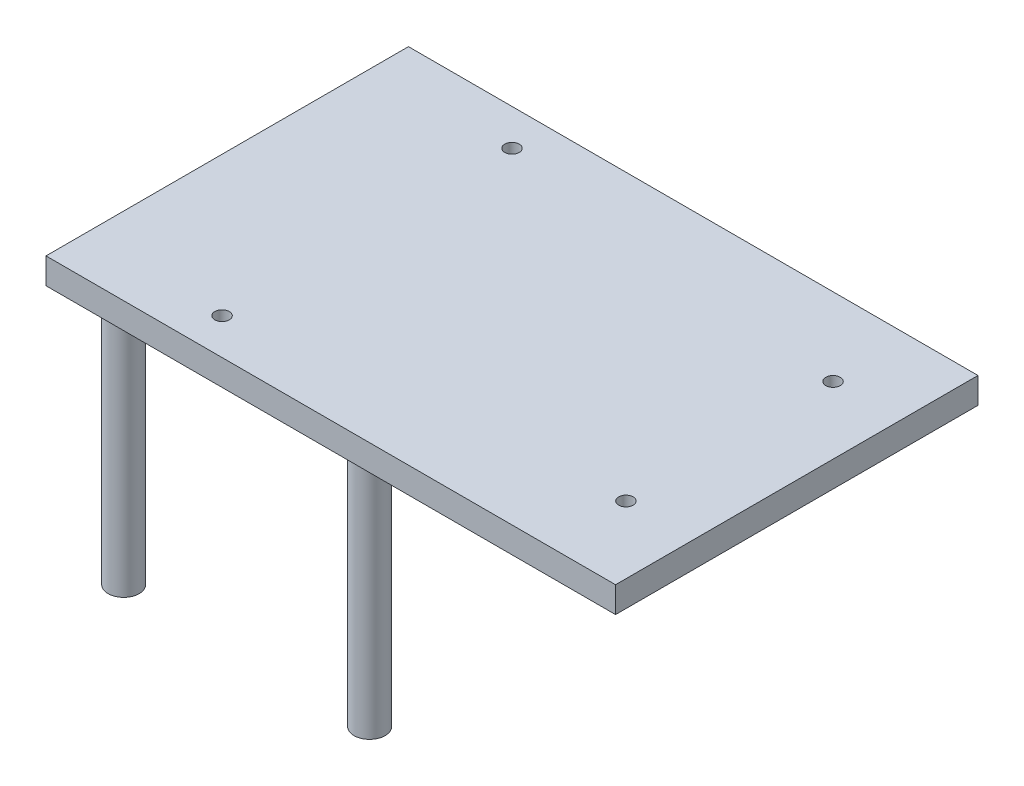
SolidWorks part; units mm, degrees
other "Markup1"
sketch "Sketch3" plane through (-55, 0, -35) normal (0, 1, 0) x (1, 0, 0)
other "DetailItem1"
ref_plane "Front Plane" through (0, 0, 0) normal (0, 0, 1) x (1, 0, 0)
ref_plane "Top Plane" through (0, 0, 0) normal (0, 1, 0) x (1, 0, 0)
ref_plane "Right Plane" through (0, 0, 0) normal (1, 0, 0) x (0, 0, -1)
sketch "Sketch1" plane through (0, 0, 0) normal (0, 1, 0) x (1, 0, 0)
  line L1 (-55, 35) -> (55, 35)
  line L2 (-55, 35) -> (-55, -35)
  line L3 (-55, -35) -> (55, -35)
  line L4 (55, 35) -> (55, -35)
  line L5 (-55, 35) -> (55, -35) construction
  line L6 (-55, -35) -> (55, 35) construction
  dimension "D1" = 70
  dimension "D2" = 110
extrude "Boss-Extrude2" add sketch "Sketch1" against normal blind 5
sketch "Sketch2" plane through (0, 0, 0) normal (0, 1, 0) x (1, 0, 0)
  line L0 (-28, 28) -> (-28, -28) construction
  line L1 (42, 20) -> (42, -20) construction
  circle A8 centre (-28, 28) radius 1.4
  circle A9 centre (42, 20) radius 1.4
  circle A10 centre (-28, -28) radius 1.4
  circle A11 centre (42, -20) radius 1.4
  point P12 (42, 0)
  point P15 (-28, 0)
  dimension "D1" = 56
  dimension "D5" = 2.8
  dimension "D6" = 2.8
  dimension "D7" = 2.8
  dimension "D8" = 2.8
  dimension "D2" = 40
  dimension "D3" = 28
  dimension "D4" = 42
extrude "Cut-Extrude1" cut sketch "Sketch2" against normal blind 5
sketch "Sketch4" plane through (0, -5, 0) normal (0, -1, 0) x (1, 0, 0)
  line L0 (-55, -35) -> (-55, 35) construction
  line L1 (-55, 35) -> (55, 35) construction
  line L3 (2.75, 0) -> (-2.75, 0) construction
  circle A0 centre (-47.5, 27.5) radius 3
  circle A2 centre (0, 27.5) radius 3
  circle A4 centre (0, -27.5) radius 3
  circle A5 centre (-47.5, -27.5) radius 3
  dimension "D1" = 7.5
  dimension "D5" = 6
  dimension "D2" = 7.5
  dimension "D3" = 7.5
  dimension "D4" = 55
extrude "Boss-Extrude3" add sketch "Sketch4" along normal blind 50
sketch "Sketch5" plane through (0, -55, 0) normal (0, -1, 0) x (1, 0, 0)
  line L0 (2.75, 0) -> (-2.75, 0) construction
  circle A0 centre (-47.5, 27.5) radius 1.4
  circle A1 centre (0, 27.5) radius 1.4
  circle A2 centre (0, -27.5) radius 1.4
  circle A3 centre (-47.5, -27.5) radius 1.4
extrude "Cut-Extrude2" cut sketch "Sketch5" against normal blind 3
